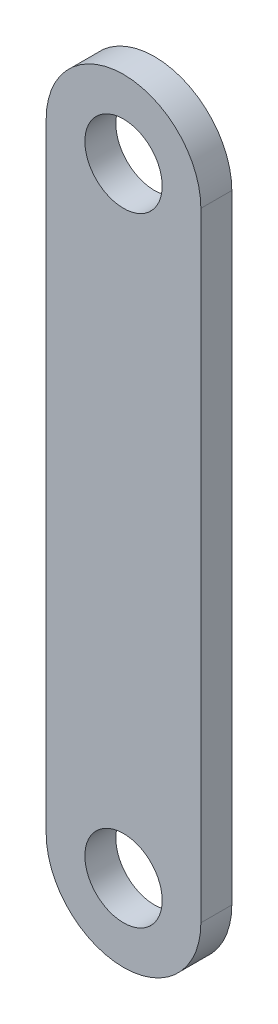
SolidWorks part; units mm, degrees
ref_plane "前视基准面" through (0, 0, 0) normal (0, 0, 1) x (1, 0, 0)
ref_plane "上视基准面" through (0, 0, 0) normal (0, 1, 0) x (1, 0, 0)
ref_plane "右视基准面" through (0, 0, 0) normal (1, 0, 0) x (0, 0, -1)
sketch "草图2" plane through (0, 0, 0) normal (0, 0, 1) x (1, 0, 0)
  line L0 (0, 7.5) -> (0, 47.5) construction
  line L1 (-5, 7.5) -> (-5, 47.5)
  line L2 (5, 7.5) -> (5, 47.5)
  arc A0 (-5, 7.5) -> (5, 7.5) centre (0, 7.5) ccw
  arc A1 (5, 47.5) -> (-5, 47.5) centre (0, 47.5) ccw
  circle A2 centre (0, 7.5) radius 2.5
  circle A3 centre (0, 47.5) radius 2.5
  point P3 (0, 27.5)
  dimension "D2" = 5
  dimension "D3" = 5
  dimension "D1" = 40
extrude "凸台-拉伸1" add sketch "草图2" along normal blind 2
